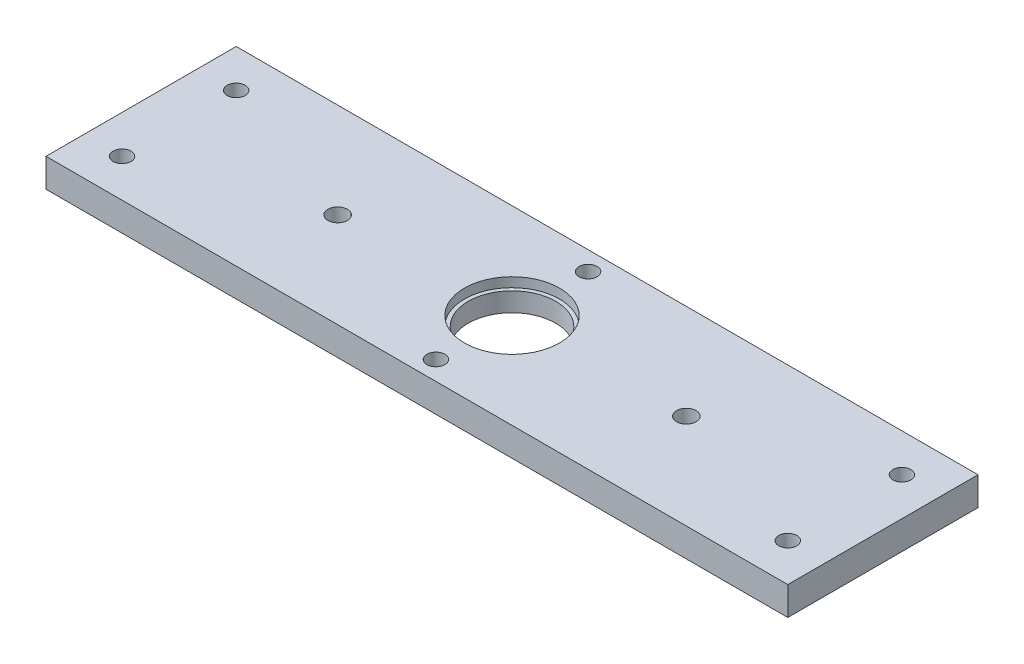
SolidWorks part; units mm, degrees
ref_plane "Front Plane" through (0, 0, 0) normal (0, 0, 1) x (1, 0, 0)
ref_plane "Top Plane" through (0, 0, 0) normal (0, 1, 0) x (1, 0, 0)
ref_plane "Right Plane" through (0, 0, 0) normal (1, 0, 0) x (0, 0, -1)
sketch "Sketch1" plane through (0, 0, 0) normal (0, 1, 0) x (1, 0, 0)
  line L1 (-123.825, -31.75) -> (123.825, -31.75)
  line L2 (-123.825, -31.75) -> (-123.825, 31.75)
  line L3 (-123.825, 31.75) -> (123.825, 31.75)
  line L4 (123.825, -31.75) -> (123.825, 31.75)
  line L5 (-123.825, -31.75) -> (123.825, 31.75) construction
  line L6 (-123.825, 31.75) -> (123.825, -31.75) construction
  point P0 (0, 0)
  dimension "D1" = 247.65
  dimension "D2" = 63.5
extrude "Boss-Extrude1" add sketch "Sketch1" along normal blind 9.525
sketch "Sketch2" plane through (0, 9.525, 0) normal (0, 1, 0) x (1, 0, 0)
  line L0 (-41.275, -31.75) -> (-41.275, 31.75)
  line L1 (-123.825, -31.75) -> (123.825, -31.75) construction
  line L2 (123.825, 31.75) -> (-123.825, 31.75) construction
  line L3 (-123.825, 31.75) -> (-123.825, -31.75) construction
  line L4 (41.275, 31.75) -> (41.275, -31.75)
  line L5 (123.825, -31.75) -> (123.825, 31.75) construction
  dimension "D1" = 82.55
  dimension "D2" = 82.55
sketch "Sketch3" plane through (0, 9.525, 0) normal (0, 1, 0) x (1, 0, 0)
  circle A0 centre (0, 0) radius 14.605
  dimension "D1" = 29.21
extrude "Cut-Extrude1" cut sketch "Sketch3" against normal through all
sketch "Sketch6" plane through (0, 0, 31.75) normal (0, 0, 1) x (1, 0, 0)
  line L0 (-41.275, 9.525) -> (-41.275, 0)
  line L1 (-123.825, 0) -> (123.825, 0) construction
sketch "Sketch7" plane through (0, 0, 0) normal (0, -1, 0) x (1, 0, 0)
  line L0 (-41.275, 31.75) -> (-41.275, -31.75)
  line L1 (123.825, -31.75) -> (-123.825, -31.75) construction
sketch "Sketch8" plane through (0, 0, 31.75) normal (0, 0, 1) x (1, 0, 0)
  line L0 (41.275, 9.525) -> (41.275, 0)
  line L1 (-123.825, 0) -> (123.825, 0) construction
sketch "Sketch9" plane through (0, 0, 0) normal (0, -1, 0) x (1, 0, 0)
  line L0 (41.275, 31.75) -> (41.275, -31.75)
  line L1 (123.825, -31.75) -> (-123.825, -31.75) construction
hole_wizard "Ø6.0 (6) Diameter Hole1" positions "Sketch22" profile "Sketch23" hole size "Ø6.0" standard "ANSI Metric" end condition through all
sketch "Sketch22" plane through (0, 0, 0) normal (0, -1, 0) x (-1, 0, 0)
  point P0 (0, -25.4)
  point P2 (0, 25.4)
  dimension "D1" = 25.4
  dimension "D2" = 25.4
sketch "Sketch23" plane through (0, 0, 25.4) normal (1, 0, 0) x (0, 0, -1)
  line L0 (0, 0) -> (0, 9.525)
  line L1 (0, 9.525) -> (3, 9.525)
  line L2 (3, 9.525) -> (3, 0)
  line L5 (3, 0) -> (0, 0)
  line L11 (0, -6.35) -> (0, 107.95) construction
  dimension "Thru Hole Dia." = 6
  dimension "Thru Hole Depth" = 9.525
hole_wizard "Ø6.5 (6.5) Diameter Hole3" positions "Sketch24" profile "Sketch25" hole size "Ø6.5" standard "ANSI Metric" end condition through all
sketch "Sketch24" plane through (0, 0, 0) normal (0, -1, 0) x (-1, 0, 0)
  line L0 (41.275, -31.75) -> (41.275, 31.75) construction
  line L1 (-41.275, 31.75) -> (-41.275, -31.75) construction
  point P0 (58.2083, 0)
  point P2 (-58.2083, 0)
  dimension "D1" = 16.9333
  dimension "D2" = 16.9333
sketch "Sketch25" plane through (-58.2083, 0, 0) normal (1, 0, 0) x (0, 0, -1)
  line L0 (0, 0) -> (0, 9.525)
  line L1 (0, 9.525) -> (3.25, 9.525)
  line L2 (3.25, 9.525) -> (3.25, 0)
  line L5 (3.25, 0) -> (0, 0)
  line L11 (0, -6.35) -> (0, 107.95) construction
  dimension "Thru Hole Dia." = 6.5
  dimension "Thru Hole Depth" = 9.525
sketch "Sketch29" plane through (0, 9.525, 0) normal (0, 1, 0) x (1, 0, 0)
  circle A0 centre (0, 0) radius 15.875
extrude "Cut-Extrude5" cut sketch "Sketch29" against normal blind 3.175
hole_wizard "Ø6.0 (6) Diameter Hole3" positions "Sketch32" profile "Sketch31" hole size "Ø6.0" standard "ANSI Metric" end condition through all
sketch "Sketch32" plane through (0, 9.525, 0) normal (0, 1, 0) x (1, 0, 0)
  line L0 (123.825, 31.75) -> (-123.825, 31.75) construction
  line L1 (-123.825, 31.75) -> (-123.825, -31.75) construction
  line L2 (-123.825, -31.75) -> (123.825, -31.75) construction
  line L3 (123.825, -31.75) -> (123.825, 31.75) construction
  point P0 (-111.125, 19.05)
  point P2 (-111.125, -19.05)
  point P4 (111.125, -19.05)
  point P6 (111.125, 19.05)
  dimension "D1" = 12.7
  dimension "D2" = 12.7
  dimension "D3" = 12.7
  dimension "D4" = 12.7
  dimension "D5" = 12.7
  dimension "D6" = 12.7
  dimension "D7" = 12.7
  dimension "D8" = 12.7
sketch "Sketch31" plane through (-111.125, 9.525, -19.05) normal (1, 0, 0) x (0, 0, 1)
  line L0 (0, 0) -> (0, 9.525)
  line L1 (0, 9.525) -> (3, 9.525)
  line L2 (3, 9.525) -> (3, 0)
  line L5 (3, 0) -> (0, 0)
  line L11 (0, -6.35) -> (0, 107.95) construction
  dimension "Thru Hole Dia." = 6
  dimension "Thru Hole Depth" = 9.525
